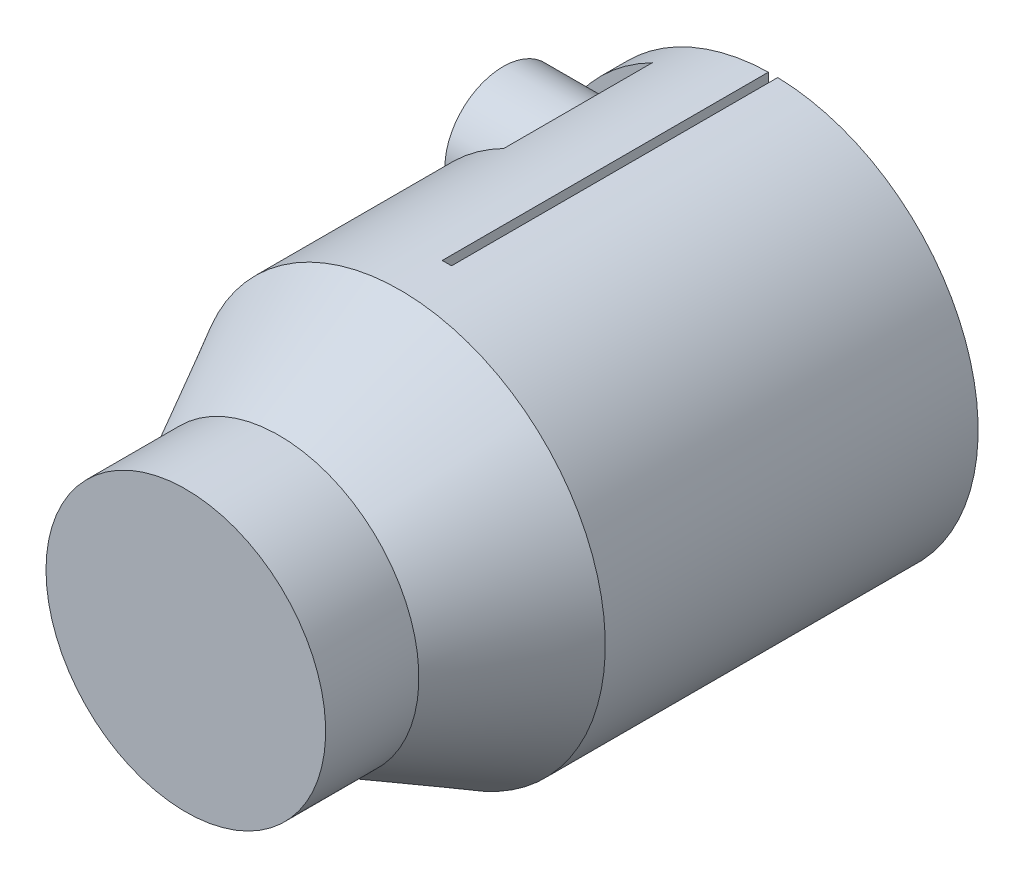
SolidWorks part; units mm, degrees
material "1.0553 (S355J0)"
ref_plane "Płaszczyzna przednia" through (0, 0, 0) normal (0, 0, 1) x (1, 0, 0)
ref_plane "Płaszczyzna górna" through (0, 0, 0) normal (0, 1, 0) x (1, 0, 0)
ref_plane "Płaszczyzna prawa" through (0, 0, 0) normal (1, 0, 0) x (0, 0, -1)
sketch "Szkic2" plane through (0, 0, 0) normal (0, 1, 0) x (1, 0, 0)
  line L0 (0, -40) -> (7, -53)
  line L1 (0, 0) -> (44, 0)
  line L2 (0, 0) -> (0, -40)
  line L4 (44, 0) -> (44, -40)
  line L5 (15, 0) -> (29, 0)
  line L6 (15, 0) -> (15, -40)
  line L7 (15, -40) -> (29, -40)
  line L8 (29, 0) -> (29, -40)
  line L10 (37, -53) -> (44, -40)
  line L11 (22, 0) -> (22, -88.1836) construction
  line L13 (7, -53) -> (7, -63)
  line L14 (7, -63) -> (37, -63)
  line L15 (37, -53) -> (37, -63)
  point P13 (22, -40)
  point P17 (22, -63)
  dimension "D1" = 44
  dimension "D2" = 40
  dimension "D3" = 14
  dimension "D4" = 63
  dimension "D5" = 30
  dimension "D6" = 10
  dimension "D7" = 40
revolve "Obrót1" add sketch "Szkic2" angle 360 about L11
sketch "Szkic3" plane through (0, 0, 0) normal (0, 0, -1) x (-1, 0, 0)
  line L0 (-22, -22) -> (-22, 34.8327) construction
  line L1 (-22.5, 5.0248) -> (-21.5, 5.0248)
  line L2 (-22.5, 5.0248) -> (-22.5, 22.5534)
  line L3 (-22.5, 22.5534) -> (-21.5, 22.5534)
  line L4 (-21.5, 5.0248) -> (-21.5, 22.5534)
  circle A0 centre (-22, 0) radius 22 construction
  point P9 (-22, 22.5534)
  dimension "D1" = 1
extrude "Wytnij-wyciągnięcie1" cut sketch "Szkic3" against normal blind 35
sketch "Szkic4" plane through (0, 0, 0) normal (1, 0, 0) x (0, 0, -1)
  line L0 (0, 21.9943) -> (-71.781, 21.9943) construction
  circle A0 centre (-10.9568, 12.9943) radius 6.4
  dimension "D2" = 12.8
  dimension "D1" = 9
sketch "Szkic9" plane through (0, 0, 0) normal (1, 0, 0) x (0, 0, -1)
  line L2 (-2.9568, 12.9943) -> (-2.9568, 31.0113)
  line L3 (-2.9568, 31.0113) -> (-18.8951, 31.0113)
  line L4 (-18.8951, 12.002) -> (-18.8951, 31.0113)
  arc A0 (-18.8951, 12.002) -> (-2.9568, 12.9943) centre (-10.9568, 12.9943) ccw
extrude "Wytnij-wyciągnięcie4" cut sketch "Szkic9" along normal blind 12
sketch "Szkic10" plane through (12, 0, 0) normal (-1, 0, 0) x (0, 0, 1)
  circle A0 centre (10.9568, 12.9943) radius 6.25
  dimension "D1" = 12.5
extrude "Dodanie-wyciągnięcie5" add sketch "Szkic10" along normal blind 8
sketch "Szkic11" plane through (4, 0, 0) normal (-1, 0, 0) x (0, 0, 1)
  line L1 (14.3607, 12.3509) -> (13.216, 15.6204)
  line L2 (13.216, 15.6204) -> (9.8121, 16.2638)
  line L3 (9.8121, 16.2638) -> (7.553, 13.6377)
  line L4 (7.553, 13.6377) -> (8.6977, 10.3682)
  line L5 (8.6977, 10.3682) -> (12.1015, 9.7248)
  line L6 (12.1015, 9.7248) -> (14.3607, 12.3509)
  circle A0 centre (10.9568, 12.9943) radius 3 construction
  dimension "D1" = 6
extrude "Wytnij-wyciągnięcie5" cut sketch "Szkic11" against normal blind 5
sketch "Szkic12" plane through (9, 0, 0) normal (-1, 0, 0) x (0, 0, 1)
  circle A0 centre (10.9568, 12.9943) radius 4
  dimension "D1" = 8
extrude "Dodanie-wyciągnięcie6" add sketch "Szkic12" against normal blind 23
